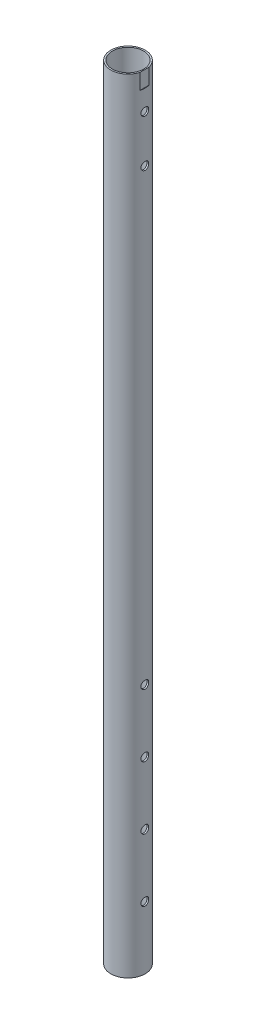
SolidWorks part; units mm, degrees
material "Custom Plastic"
ref_plane "Front Plane" through (0, 0, 0) normal (0, 0, 1) x (1, 0, 0)
ref_plane "Top Plane"
ref_plane "Right Plane" through (0, 0, 0) normal (1, 0, 0) x (0, 0, -1)
sketch "Sketch1" plane through (0, 0, 0) normal (0, 1, 0) x (1, 0, 0)
  circle A0 centre (0, 0) radius 11
  circle A1 centre (0, 0) radius 10
  dimension "D1" = 22
  dimension "D2" = 20
extrude "Boss-Extrude1" add sketch "Sketch1" along normal blind 500
sketch "Sketch2" plane through (0, 500, 0) normal (0, 1, 0) x (1, 0, 0)
  line L1 (11.4, 2.9392) -> (10.6, 2.9392)
  line L2 (11.4, 2.9392) -> (11.4, -2.9392)
  line L3 (11.4, -2.9392) -> (10.6, -2.9392)
  line L4 (10.6, 2.9392) -> (10.6, -2.9392)
  line L5 (11.4, 2.9392) -> (10.6, -2.9392) construction
  line L6 (11.4, -2.9392) -> (10.6, 2.9392) construction
  circle A0 centre (0, 0) radius 11 construction
  point P0 (11, 0)
  dimension "D1" = 0.7999
extrude "Cut-Extrude1" cut sketch "Sketch2" against normal blind 10
sketch "Sketch3" plane through (10.6, 0, 0) normal (1, 0, 0) x (0, 0, -1)
  line L0 (11, 500) -> (-11, 500) construction
  circle A0 centre (0, 477) radius 2.5
  circle A1 centre (0, 447) radius 2.5
  point P4 (0, 0)
  point P7 (0, 0)
  dimension "D1" = 5
  dimension "D2" = 5
  dimension "D3" = 30
  dimension "D4" = 23
extrude "Cut-Extrude2" cut sketch "Sketch3" against normal through all both and the other way through all
sketch "Sketch5" plane through (10.6, 0, 0) normal (1, 0, 0) x (0, 0, -1)
  line L0 (-11, 0) -> (11, 0) construction
  circle A0 centre (0, 40) radius 2.5
  circle A1 centre (0, 80) radius 2.5
  circle A2 centre (0, 120) radius 2.5
  circle A3 centre (0, 160) radius 2.5
  dimension "D1" = 5
  dimension "D2" = 40
  dimension "D3" = 4
extrude "Cut-Extrude3" cut sketch "Sketch5" against normal through all both and the other way through all
